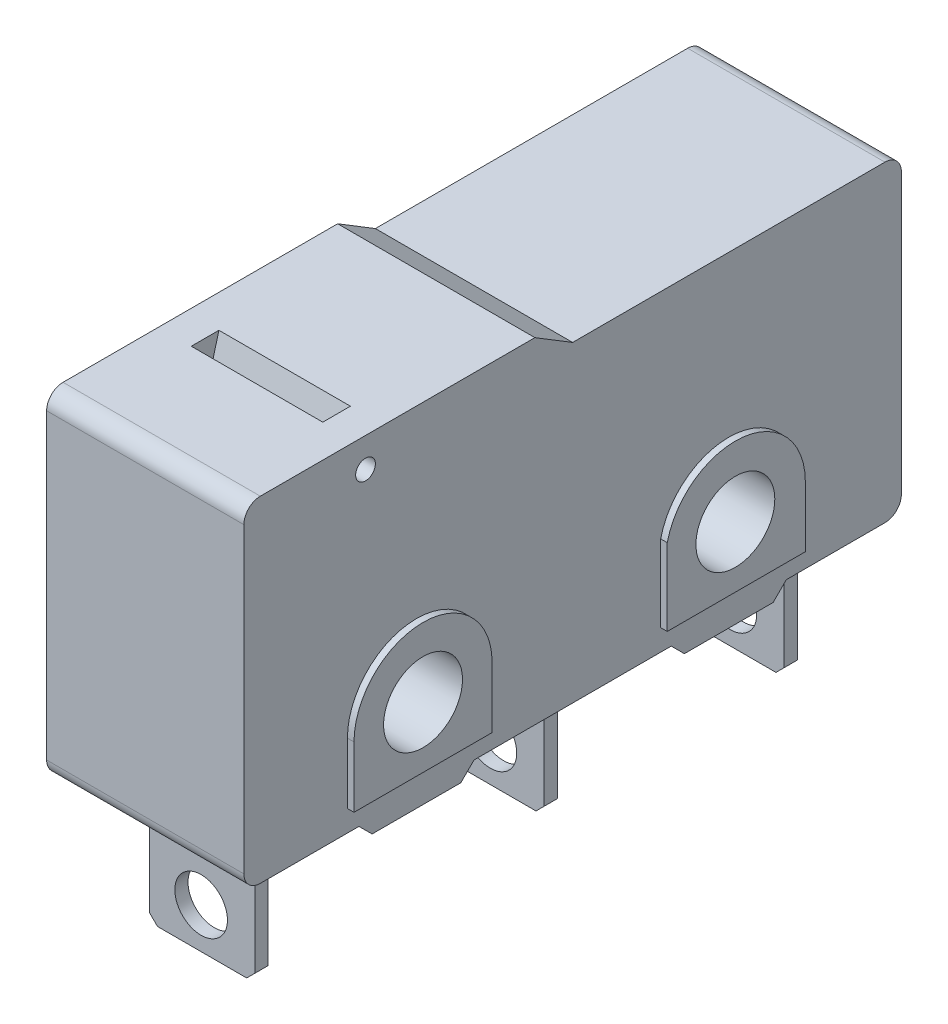
SolidWorks part; units mm, degrees
ref_plane "Front Plane" through (0, 0, 0) normal (0, 0, 1) x (1, 0, 0)
ref_plane "Top Plane" through (0, 0, 0) normal (0, 1, 0) x (1, 0, 0)
ref_plane "Right Plane" through (0, 0, 0) normal (1, 0, 0) x (0, 0, -1)
sketch "Sketch1" plane through (0, 0, 0) normal (1, 0, 0) x (0, 0, -1)
  line L0 (10, 4.4) -> (0, 4.4)
  line L2 (10, 4.4) -> (10, -5.1)
  line L4 (-10, 5.1) -> (-10, -5.1)
  line L5 (0, 4.4) -> (-1.1476, 5.1)
  line L6 (10, -5.1) -> (-10, 5.1) construction
  line L7 (-1.1476, 5.1) -> (-10, 5.1)
  line L8 (-10, -5.1) -> (-6.5, -5.1)
  line L12 (-3, -5.1) -> (3, -5.1)
  line L16 (6.5, -5.1) -> (10, -5.1)
  line L17 (-6.5, -5.1) -> (-6.1, -5.5)
  line L18 (-6.1, -5.5) -> (-3.4, -5.5)
  line L19 (-3.4, -5.5) -> (-3, -5.1)
  line L20 (6.5, -5.1) -> (6.1, -5.5)
  line L21 (3, -5.1) -> (3.4, -5.5)
  line L23 (3.4, -5.5) -> (6.1, -5.5)
  point P0 (0, 0)
  dimension "D1" = 20
  dimension "D2" = 10.2
  dimension "D3" = 9.5
  dimension "D4" = 20
  dimension "D5" = 3.5
  dimension "D6" = 0.4
  dimension "D7" = 45
  dimension "D8" = 45
  dimension "D9" = 45
  dimension "D10" = 0.4
  dimension "D11" = 45
  dimension "D12" = 6
extrude "Boss-Extrude1" add sketch "Sketch1" along normal mid plane 6
sketch "Sketch5" plane through (0, -5.1, 0) normal (0, -1, 0) x (1, 0, 0)
  line L0 (-1.5777, 8.3) -> (1.6361, 8.3)
  line L1 (1.6361, 8.3) -> (1.6361, 7.9)
  line L2 (1.6361, 7.9) -> (-1.5777, 7.9)
  line L3 (-1.5777, 7.9) -> (-1.5777, 8.3)
  line L4 (-1.5777, -0.5) -> (1.6361, -0.5)
  line L5 (1.6361, -0.5) -> (1.6361, -0.9)
  line L6 (1.6361, -0.9) -> (-1.5777, -0.9)
  line L7 (-1.5777, -0.9) -> (-1.5777, -0.5)
  line L8 (-1.5777, -7.8) -> (1.6361, -7.8)
  line L9 (1.6361, -7.8) -> (1.6361, -8.2)
  line L10 (1.6361, -8.2) -> (-1.5777, -8.2)
  line L11 (-1.5777, -8.2) -> (-1.5777, -7.8)
  line L12 (3, 10) -> (-3, 10) construction
  dimension "D1" = 1.7
  dimension "D2" = 0.4
  dimension "D3" = 8.8
  dimension "D4" = 7.3
extrude "Boss-Extrude2" add sketch "Sketch5" along normal blind 3.9
chamfer "Chamfer2" distance 0.25 angle 45 6 edges at (-1.5777, -9, 8.1) (1.6361, -9, -8) (-1.5777, -9, -8) (1.6361, -9, -0.7) (-1.5777, -9, -0.7) (1.6361, -9, 8.1)
sketch "Sketch6" plane through (0, 0, 8.3) normal (0, 0, 1) x (1, 0, 0)
  line L0 (0, -55) -> (0, 55) construction
  circle A0 centre (0, -7.7687) radius 0.8
  dimension "D1" = 1.6
extrude "Cut-Extrude1" cut sketch "Sketch6" against normal through all
fillet "Fillet1" radius 0.5 4 edges at (0, -5.1, -10) (0, 4.4, -10) (0, -5.1, 10) (0, 5.1, 10)
sketch "Sketch7" plane through (3, 0, 0) normal (1, 0, 0) x (0, 0, -1)
  line L0 (-10, 4.6) -> (-10, -4.6) construction
  line L1 (-9.5, -5.1) -> (-6.5, -5.1) construction
  circle A0 centre (-4.75, -2.6) radius 1.2
  circle A1 centre (4.75, -2.6) radius 1.2
  dimension "D3" = 2.4
  dimension "D1" = 5.25
  dimension "D2" = 9.5
  dimension "D4" = 2.5
extrude "Cut-Extrude2" cut sketch "Sketch7" against normal through all
sketch "Sketch11" plane through (0, 0, 0) normal (1, 0, 0) x (0, 0, -1)
  line L0 (-6.85, -4.4534) -> (-2.65, -4.4534)
  line L1 (-2.65, -4.4534) -> (-2.65, -2.6)
  line L2 (-6.85, -2.6) -> (-6.85, -4.4534)
  line L3 (2.6782, -4.4534) -> (6.8782, -4.4534)
  line L4 (6.8782, -4.4534) -> (6.8782, -2.6)
  line L5 (2.6782, -2.1134) -> (2.6782, -4.4534)
  circle A0 centre (-4.75, -2.6) radius 1.2
  circle A1 centre (4.75, -2.6) radius 1.2
  arc A2 (-2.65, -2.6) -> (-6.85, -2.6) centre (-4.75, -2.6) ccw
  arc A3 (6.8782, -2.6) -> (2.6782, -2.1134) centre (4.75, -2.6) ccw
  dimension "D1" = 4.2
extrude "Boss-Extrude5" add sketch "Sketch11" along normal blind 3.2 and the other way blind 3.4
sketch "Sketch12" plane through (3, 0, 0) normal (1, 0, 0) x (0, 0, -1)
  line L0 (10, -4.6) -> (10, 3.9) construction
  circle A0 centre (-6.3, 4.202) radius 0.3
  dimension "D1" = 0.6
  dimension "D2" = 16.3
extrude "Cut-Extrude3" cut sketch "Sketch12" against normal through all
sketch "Sketch13" plane through (0, 0, 0) normal (1, 0, 0) x (0, 0, -1)
  line L0 (-6.6, 4.202) -> (-6.6, 5.1)
  line L1 (-1.1476, 5.1) -> (-9.5, 5.1) construction
  line L2 (-6.6, 5.1) -> (-5.7594, 5.1)
  line L3 (-5.7594, 5.1) -> (-6, 4.202)
  line L4 (-6, 4.202) -> (-6.6, 4.202)
  circle A0 centre (-6.3, 4.202) radius 0.3 construction
  dimension "D1" = 75
extrude "Cut-Extrude4" cut sketch "Sketch13" against normal blind 2 and the other way blind 2
